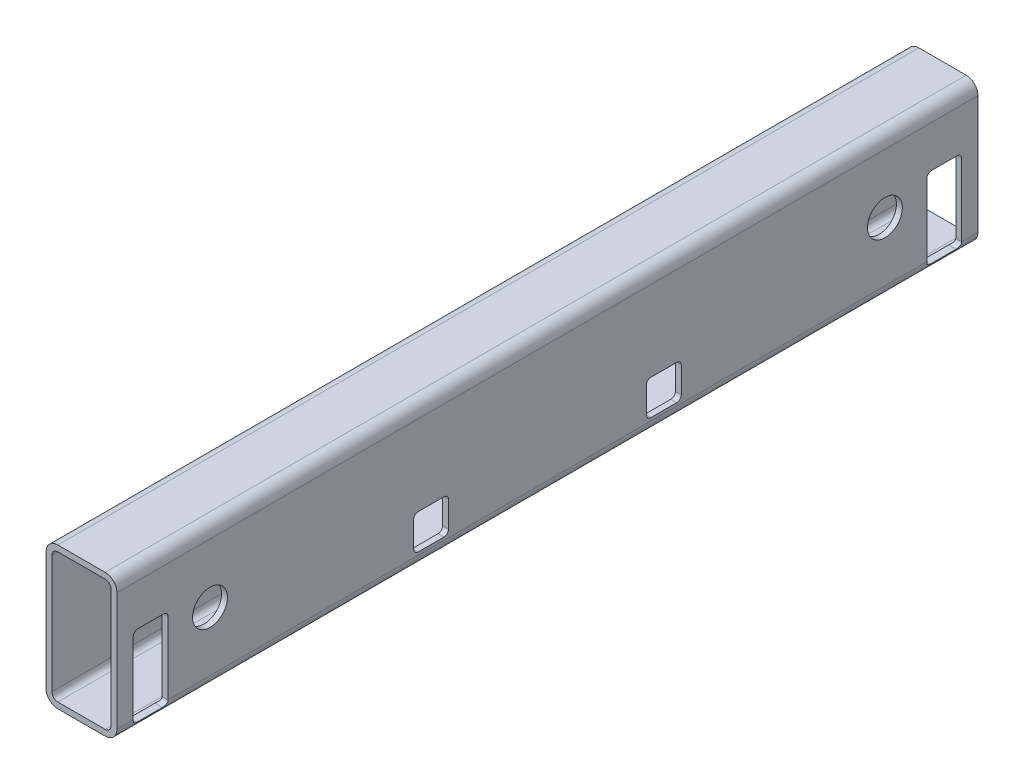
SolidWorks part; units mm, degrees
material "Low Carbon Steel"
ref_plane "Front Plane" through (0, 0, 0) normal (0, 0, 1) x (1, 0, 0)
ref_plane "Top Plane" through (0, 0, 0) normal (0, 1, 0) x (1, 0, 0)
ref_plane "Right Plane" through (0, 0, 0) normal (1, 0, 0) x (0, 0, -1)
sketch "Sketch1" plane through (0, 0, 0) normal (0, 0, 1) x (1, 0, 0)
  line L0 (-50.8, -139.7) -> (50.8, -139.7)
  line L1 (-63.5, -127) -> (-63.5, 127)
  line L2 (50.8, 139.7) -> (-50.8, 139.7)
  line L3 (63.5, 127) -> (63.5, -127)
  line L4 (-50.8, -152.4) -> (50.8, -152.4)
  line L5 (-76.2, -127) -> (-76.2, 127)
  line L6 (50.8, 152.4) -> (-50.8, 152.4)
  line L7 (76.2, 127) -> (76.2, -127)
  line L8 (-50.8, -127) -> (50.8, 127) construction
  arc A0 (76.2, 127) -> (50.8, 152.4) centre (50.8, 127) ccw
  arc A1 (50.8, -152.4) -> (76.2, -127) centre (50.8, -127) ccw
  arc A2 (-76.2, -127) -> (-50.8, -152.4) centre (-50.8, -127) ccw
  arc A3 (-50.8, 152.4) -> (-76.2, 127) centre (-50.8, 127) ccw
  arc A4 (-50.8, 139.7) -> (-63.5, 127) centre (-50.8, 127) ccw
  arc A5 (63.5, 127) -> (50.8, 139.7) centre (50.8, 127) ccw
  arc A6 (50.8, -139.7) -> (63.5, -127) centre (50.8, -127) ccw
  arc A7 (-63.5, -127) -> (-50.8, -139.7) centre (-50.8, -127) ccw
extrude "Boss-Extrude1" add sketch "Sketch1" along normal mid plane 1850
sketch "Sketch2" plane through (76.2, 0, 0) normal (1, 0, 0) x (0, 0, -1)
  line L0 (-925, -127) -> (-925, 127) construction
  line L1 (-880, 37.6) -> (-825, 37.6)
  line L2 (-890, 27.6) -> (-890, -127.4)
  line L3 (-880, -137.4) -> (-825, -137.4)
  line L4 (-815, 27.6) -> (-815, -127.4)
  line L5 (825, 37.6) -> (880, 37.6)
  line L6 (815, 27.6) -> (815, -127.4)
  line L7 (825, -137.4) -> (880, -137.4)
  line L8 (890, 27.6) -> (890, -127.4)
  line L9 (-925, -152.4) -> (925, -152.4) construction
  line L10 (925, -127) -> (925, 127) construction
  arc A0 (-825, 37.6) -> (-815, 27.6) centre (-825, 27.6) cw
  arc A1 (-890, -127.4) -> (-880, -137.4) centre (-880, -127.4) ccw
  arc A2 (-825, -137.4) -> (-815, -127.4) centre (-825, -127.4) ccw
  arc A3 (-880, 37.6) -> (-890, 27.6) centre (-880, 27.6) ccw
  arc A4 (880, 37.6) -> (890, 27.6) centre (880, 27.6) cw
  arc A5 (815, -127.4) -> (825, -137.4) centre (825, -127.4) ccw
  arc A6 (880, -137.4) -> (890, -127.4) centre (880, -127.4) ccw
  arc A7 (825, 37.6) -> (815, 27.6) centre (825, 27.6) ccw
  dimension "D5" = 10
  dimension "D6" = 10
  dimension "D1" = 35
  dimension "D2" = 75
  dimension "D3" = 175
  dimension "D4" = 15
  dimension "D7" = 35
extrude "Cut-Extrude1" cut sketch "Sketch2" against normal blind 30
sketch "Sketch3" plane through (76.2, 0, 0) normal (1, 0, 0) x (0, 0, -1)
  line L0 (-925, -152.4) -> (925, -152.4) construction
  line L1 (-277.5, -45.65) -> (-222.5, -45.65)
  line L2 (-287.5, -55.65) -> (-287.5, -110.65)
  line L3 (-277.5, -120.65) -> (-222.5, -120.65)
  line L4 (-212.5, -55.65) -> (-212.5, -110.65)
  line L5 (222.5, -45.65) -> (277.5, -45.65)
  line L6 (212.5, -55.65) -> (212.5, -110.65)
  line L7 (222.5, -120.65) -> (277.5, -120.65)
  line L8 (287.5, -55.65) -> (287.5, -110.65)
  line L9 (-212.5, -45.65) -> (212.5, -45.65) construction
  line L10 (0, -45.65) -> (0, 0) construction
  arc A0 (-287.5, -110.65) -> (-277.5, -120.65) centre (-277.5, -110.65) ccw
  arc A1 (-222.5, -120.65) -> (-212.5, -110.65) centre (-222.5, -110.65) ccw
  arc A2 (-277.5, -45.65) -> (-287.5, -55.65) centre (-277.5, -55.65) ccw
  arc A3 (-222.5, -45.65) -> (-212.5, -55.65) centre (-222.5, -55.65) cw
  arc A4 (212.5, -110.65) -> (222.5, -120.65) centre (222.5, -110.65) ccw
  arc A5 (222.5, -45.65) -> (212.5, -55.65) centre (222.5, -55.65) ccw
  arc A6 (277.5, -45.65) -> (287.5, -55.65) centre (277.5, -55.65) cw
  arc A7 (277.5, -120.65) -> (287.5, -110.65) centre (277.5, -110.65) ccw
  dimension "D5" = 10
  dimension "D1" = 75
  dimension "D2" = 75
  dimension "D3" = 31.75
  dimension "D4" = 500
extrude "for mach shop confirm w/ programming" cut sketch "Sketch3" against normal up to next
sketch "Sketch5" plane through (-76.2, 0, 0) normal (-1, 0, 0) x (0, 0, 1)
  line L0 (725, 0) -> (-725, 0) construction
  line L1 (925, 127) -> (925, -127) construction
  circle A0 centre (725, 0) radius 37.5
  circle A1 centre (-725, 0) radius 37.5
  dimension "D1" = 75
  dimension "D2" = 200
extrude "Cut-Extrude3" cut sketch "Sketch5" against normal through all
sketch "Sketch6" plane through (-76.2, 0, 0) normal (-1, 0, 0) x (0, 0, 1)
  line L0 (-375, 0) -> (0, 0) construction
  line L1 (0, 0) -> (300, 0) construction
  line L2 (300, 0) -> (425, 0) construction
  line L3 (-925, 127) -> (-925, -127) construction
  circle A0 centre (-375, 0) radius 25
  circle A1 centre (300, 0) radius 25
  circle A2 centre (425, 0) radius 25
  dimension "D1" = 50
  dimension "D2" = 550
  dimension "D3" = 1225
  dimension "D4" = 1350
extrude "Cut-Extrude4" cut sketch "Sketch6" against normal up to next
other "Freeze***"
